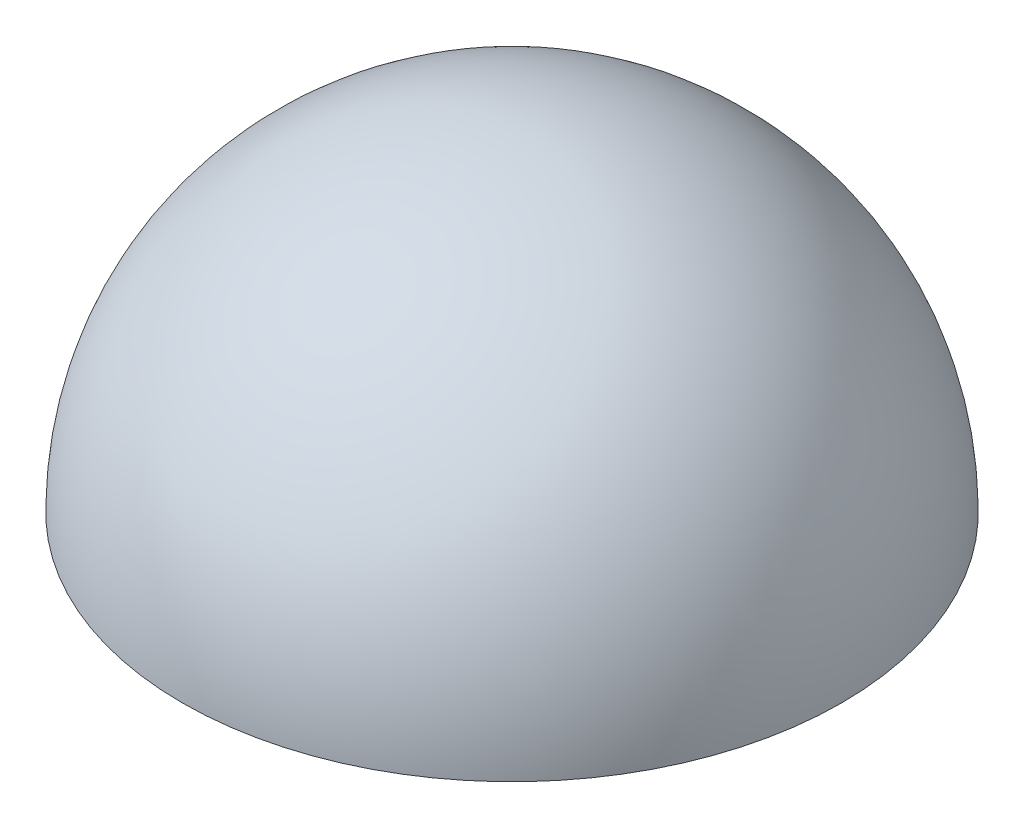
SolidWorks part; units mm, degrees
ref_plane "Front Plane" through (0, 0, 0) normal (0, 0, 1) x (1, 0, 0)
ref_plane "Top Plane" through (0, 0, 0) normal (0, 1, 0) x (1, 0, 0)
ref_plane "Right Plane" through (0, 0, 0) normal (1, 0, 0) x (0, 0, -1)
sketch "Sketch1" plane through (0, 0, 0) normal (0, 0, 1) x (1, 0, 0)
  line L0 (0, 80) -> (0, 0)
  line L1 (0, 0) -> (80, 0)
  arc A0 (0, 80) -> (80, 0) centre (0, 0) cw
  dimension "D1" = 80
  dimension "D2" = 80
revolve "Revolve3" add sketch "Sketch1" angle 360 about L0
shell "Shell9" thickness 1
